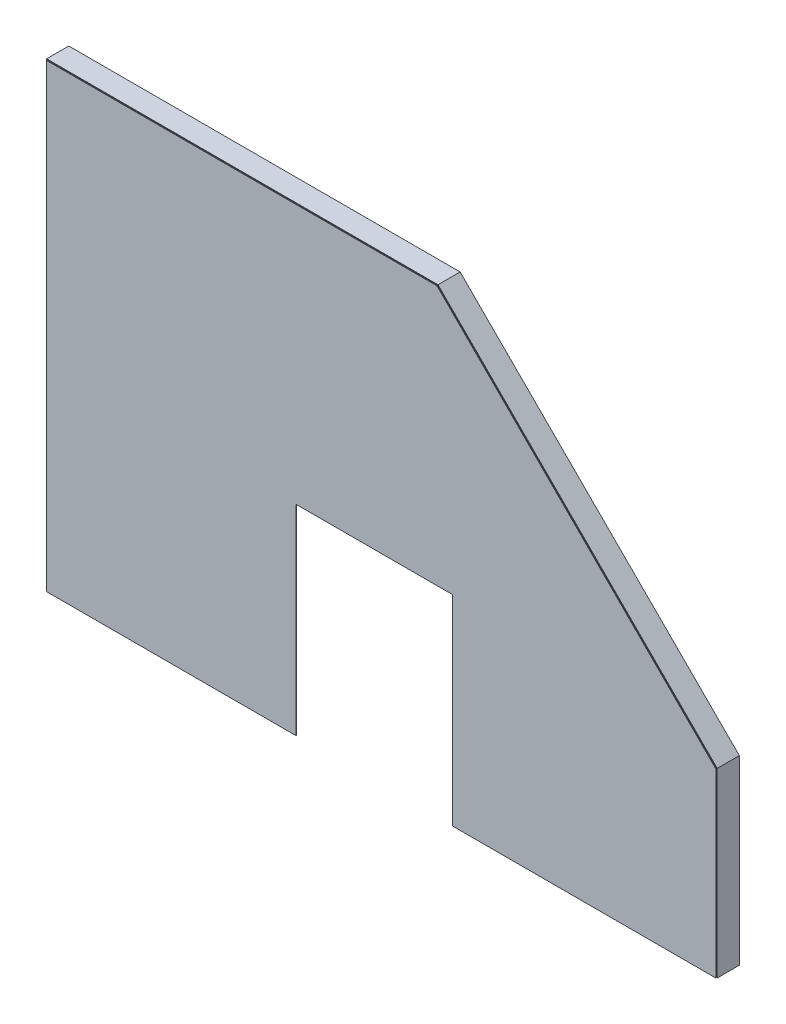
SolidWorks part; units mm, degrees
other "Elemento de detalle1"
other "Carpeta de soldadura"
other "Cordón de soldadura1"
ref_plane "Alzado" through (0, 0, 0) normal (0, 0, 1) x (1, 0, 0)
ref_plane "Planta" through (0, 0, 0) normal (0, 1, 0) x (1, 0, 0)
ref_plane "Vista lateral" through (0, 0, 0) normal (1, 0, 0) x (0, 0, -1)
sketch "Croquis1" plane through (0, 0, 0) normal (0, 0, 1) x (1, 0, 0)
  line L0 (0, 0) -> (768, 0)
  line L1 (768, 0) -> (768, 208)
  line L2 (768, 208) -> (448, 528)
  line L3 (448, 528) -> (0, 528)
  line L4 (0, 528) -> (0, 0)
  dimension "D1" = 768
  dimension "D2" = 208
  dimension "D3" = 448
  dimension "D4" = 528
extrude "Saliente-Extruir1" add sketch "Croquis1" along normal blind 0.8357
sketch "Croquis3" plane through (0, 0, 0) normal (0, 0, -1) x (-1, 0, 0)
  line L0 (0.8357, 0) -> (0.8357, 528.8357)
  line L1 (0.8357, 528.8357) -> (-448.3461, 528.8357)
  line L2 (-448.3461, 528.8357) -> (-768.8357, 208.3461)
  line L3 (-768.8357, 208.3461) -> (-768.8357, 0)
  line L4 (0.8357, 0) -> (0, 0)
  line L5 (0, 0) -> (0, 528)
  line L6 (0, 528) -> (-448, 528)
  line L7 (-448, 528) -> (-768, 208)
  line L8 (-768, 208) -> (-768, 0)
  line L9 (-768, 0) -> (0, 0)
  line L10 (0, 0) -> (0, 528)
  line L11 (0, 528) -> (-448, 528)
  line L12 (-448, 528) -> (-768, 208)
  line L13 (-768, 208) -> (-768, 0)
  line L15 (-768, 0) -> (-768.8357, 0)
  dimension "D1" = 0
  dimension "D2" = 0.8357
extrude "Saliente-Extruir2" add sketch "Croquis3" along normal blind 25.4 separate body
sketch "Croquis4" plane through (0, 0, 0.8357) normal (0, 0, 1) x (1, 0, 0)
  line L2 (286, 90) -> (286, 230)
  line L3 (286, 230) -> (466, 230)
  line L4 (466, 90) -> (466, 230)
  line L5 (0, 0) -> (768, 0) construction
  line L6 (286, 90) -> (286, 0)
  line L7 (286, 0) -> (466, 0)
  line L8 (466, 0) -> (466, 90)
  line L9 (768, 0) -> (768, 208) construction
  dimension "D1" = 180
  dimension "D2" = 302
  dimension "D3" = 90
  dimension "D4" = 230
extrude "Cortar-Extruir1" cut sketch "Croquis4" against normal blind 90
